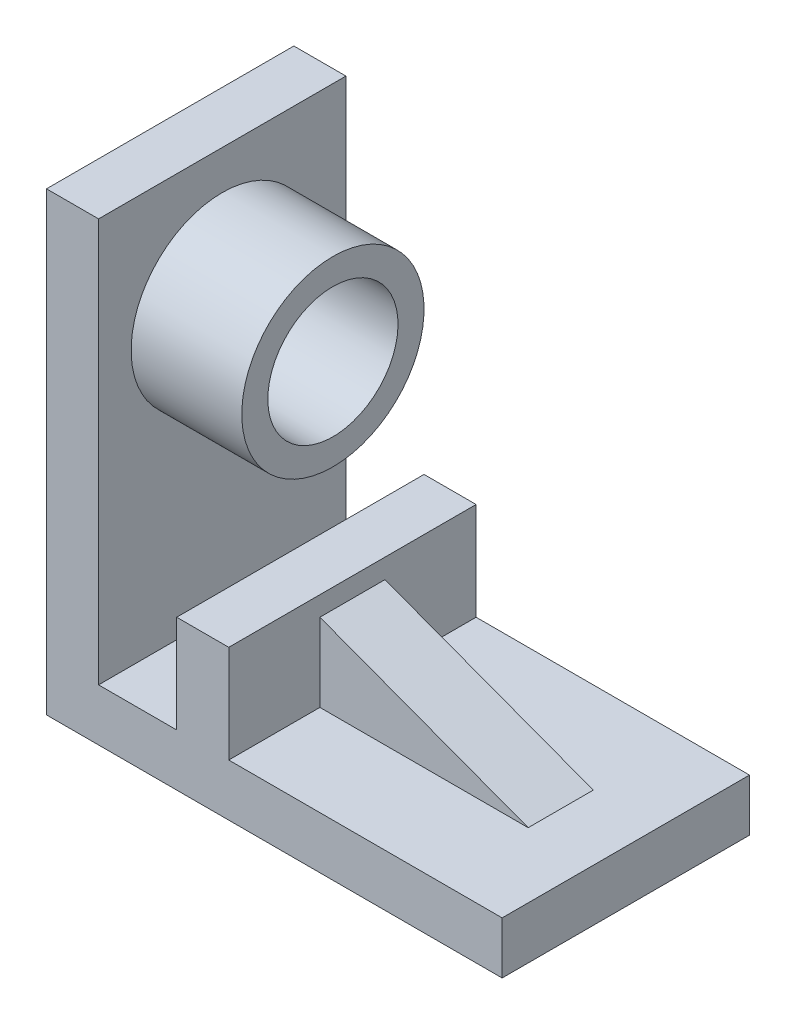
SolidWorks part; units mm, degrees
ref_plane "Front Plane" through (0, 0, 0) normal (0, 0, 1) x (1, 0, 0)
ref_plane "Top Plane" through (0, 0, 0) normal (0, 1, 0) x (1, 0, 0)
ref_plane "Right Plane" through (0, 0, 0) normal (1, 0, 0) x (0, 0, -1)
sketch "Sketch1" plane through (0, 0, 0) normal (0, 0, 1) x (1, 0, 0)
  line L0 (-16.0976, 39.8293) -> (-24.0976, 39.8293)
  line L1 (-24.0976, 39.8293) -> (-24.0976, -30.1707)
  line L2 (-24.0976, -30.1707) -> (45.9024, -30.1707)
  line L3 (45.9024, -30.1707) -> (45.9024, -22.1707)
  line L4 (45.9024, -22.1707) -> (3.9024, -22.1707)
  line L5 (3.9024, -22.1707) -> (3.9024, -7.1707)
  line L6 (3.9024, -7.1707) -> (-4.0976, -7.1707)
  line L7 (-4.0976, -7.1707) -> (-4.0976, -22.1707)
  line L8 (-4.0976, -22.1707) -> (-16.0976, -22.1707)
  line L9 (-16.0976, -22.1707) -> (-16.0976, 39.8293)
  dimension "D1" = 15
  dimension "D2" = 15
  dimension "D3" = 8
extrude "Boss-Extrude1" add sketch "Sketch1" along normal blind 38
ref_plane "Plane1" through (0, 0, 19) normal (0, 0, 1) x (1, 0, 0)
sketch "Sketch2" plane through (0, 0, 19) normal (0, 0, 1) x (1, 0, 0)
  line L0 (3.9024, -10.1707) -> (35.9024, -22.1707)
  line L1 (3.9024, -22.1707) -> (3.9024, -7.1707) construction
  line L2 (45.9024, -22.1707) -> (3.9024, -22.1707) construction
  dimension "D1" = 12
  dimension "D2" = 32
rib "Rib1" sketch "Sketch2" sketch "Sketch2" thickness 10 extrusion direction parallel to sketch draft on no parameters "D1"=10
sketch "Sketch3" plane through (-16.0976, 0, 0) normal (1, 0, 0) x (0, 0, -1)
  line L0 (-19, 38.5) -> (-19, -38.5) construction
  line L2 (-14, -22.1707) -> (0, -22.1707) construction
  circle A0 centre (-19, 19.8293) radius 14
  circle A1 centre (-19, 19.8293) radius 10
  dimension "D1" = 20
  dimension "D2" = 28
  dimension "D3" = 42
extrude "Boss-Extrude2" add sketch "Sketch3" along normal blind 17
